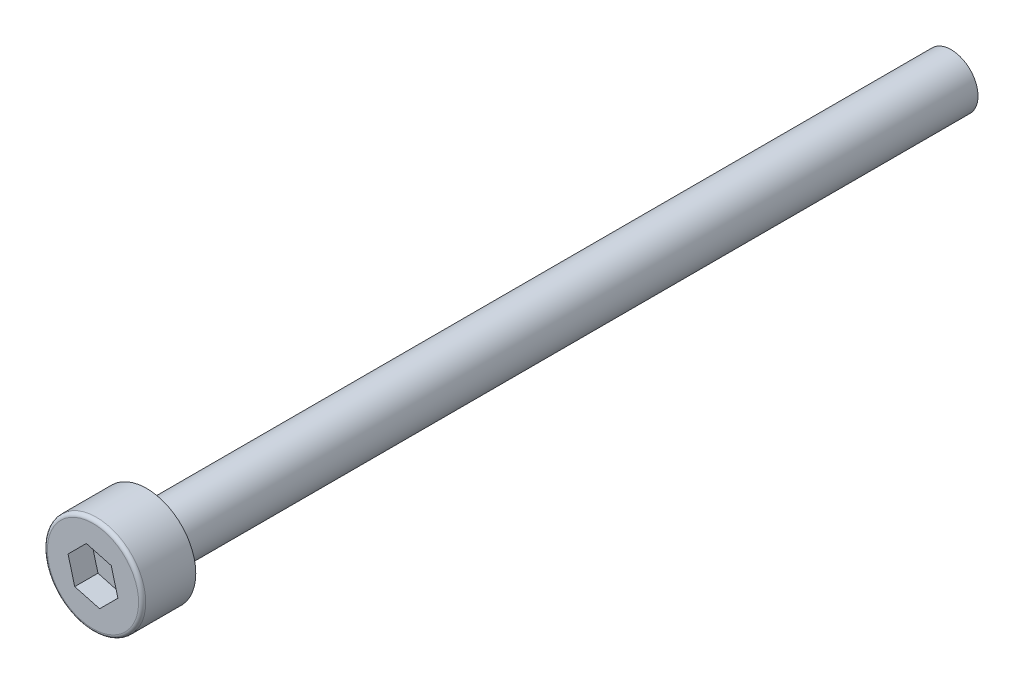
SolidWorks part; units mm, degrees
ref_plane "前视基准面" through (0, 0, 0) normal (0, 0, 1) x (1, 0, 0)
ref_plane "上视基准面" through (0, 0, 0) normal (0, 1, 0) x (1, 0, 0)
ref_plane "右视基准面" through (0, 0, 0) normal (1, 0, 0) x (0, 0, -1)
sketch "草图1" plane through (0, 0, 0) normal (0, 0, 1) x (1, 0, 0)
  circle A0 centre (0, 0) radius 2.75
  dimension "D1" = 5.5
extrude "凸台-拉伸1" add sketch "草图1" along normal blind 3
sketch "草图2" plane through (0, 0, 3) normal (0, 0, 1) x (1, 0, 0)
  line L1 (-1.0206, -1.0206) -> (0.3736, -1.3942)
  line L2 (0.3736, -1.3942) -> (1.3942, -0.3736)
  line L3 (1.3942, -0.3736) -> (1.0206, 1.0206)
  line L4 (1.0206, 1.0206) -> (-0.3736, 1.3942)
  line L5 (-0.3736, 1.3942) -> (-1.3942, 0.3736)
  line L6 (-1.3942, 0.3736) -> (-1.0206, -1.0206)
  circle A0 centre (0, 0) radius 1.25 construction
  dimension "D1" = 2.5
extrude "切除-拉伸1" cut sketch "草图2" against normal blind 1.3
sketch "草图3" plane through (0, 0, 0) normal (0, 0, -1) x (-1, 0, 0)
  circle A0 centre (0, 0) radius 1.5
  dimension "D1" = 3
extrude "凸台-拉伸2" add sketch "草图3" along normal blind 45
fillet "圆角1" radius 0.2 1 edges at (2.75, 0, 3)
